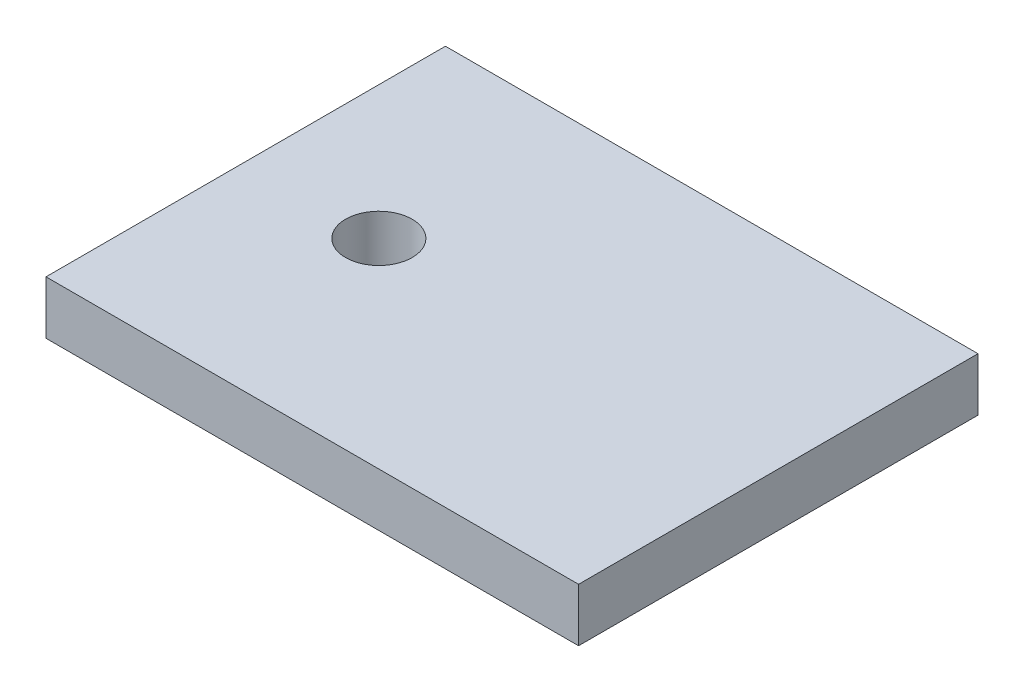
SolidWorks part; units mm, degrees
ref_plane "Front Plane" through (0, 0, 0) normal (0, 0, 1) x (1, 0, 0)
ref_plane "Top Plane" through (0, 0, 0) normal (0, 1, 0) x (1, 0, 0)
ref_plane "Right Plane" through (0, 0, 0) normal (1, 0, 0) x (0, 0, -1)
sketch "Sketch1" plane through (0, 0, 0) normal (0, 1, 0) x (1, 0, 0)
  line L1 (-20, -15) -> (20, -15)
  line L2 (-20, -15) -> (-20, 15)
  line L3 (-20, 15) -> (20, 15)
  line L4 (20, -15) -> (20, 15)
  line L5 (-20, -15) -> (20, 15) construction
  line L6 (-20, 15) -> (20, -15) construction
  point P0 (0, 0)
  dimension "D1" = 30
  dimension "D2" = 40
extrude "Boss-Extrude1" add sketch "Sketch1" along normal blind 4
sketch "Sketch2" plane through (0, 4, 0) normal (0, 1, 0) x (1, 0, 0)
  line L0 (20, -15) -> (20, 15) construction
  circle A0 centre (-10, 0) radius 2.5
  dimension "D1" = 5
  dimension "D2" = 30
extrude "Cut-Extrude1" cut sketch "Sketch2" against normal blind 4
